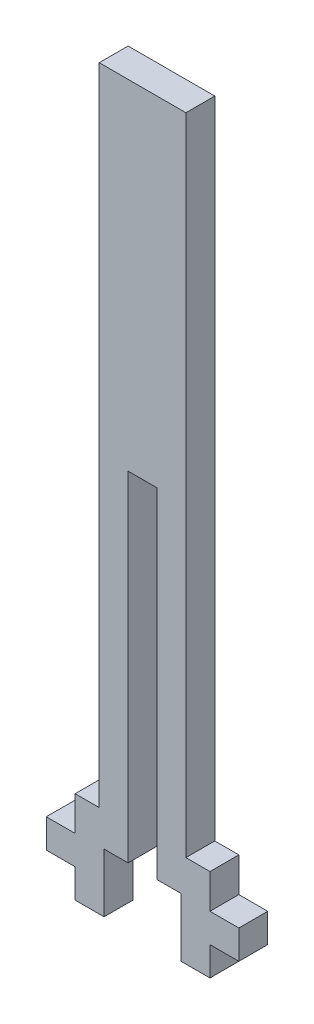
SolidWorks part; units mm, degrees
material "Plain Carbon Steel"
ref_plane "Front Plane" through (0, 0, 0) normal (0, 0, 1) x (1, 0, 0)
ref_plane "Top Plane" through (0, 0, 0) normal (0, 1, 0) x (1, 0, 0)
ref_plane "Right Plane" through (0, 0, 0) normal (1, 0, 0) x (0, 0, -1)
sketch "스케치1" plane through (0, 0, 0) normal (0, 0, 1) x (1, 0, 0)
  line L0 (0, 0) -> (0, -32.1815) construction
  line L1 (-7, -38.2815) -> (7, -38.2815) construction
  line L2 (-7, -38.2815) -> (-7, 38.2815) construction
  line L3 (-7, 38.2815) -> (7, 38.2815) construction
  line L4 (7, -38.2815) -> (7, 38.2815) construction
  line L5 (-7, -38.2815) -> (7, 38.2815) construction
  line L6 (-7, 38.2815) -> (7, -38.2815) construction
  line L7 (-4, -38.2815) -> (4, -38.2815) construction
  line L8 (-4, -38.2815) -> (-4, -32.1815)
  line L9 (-4, -32.1815) -> (4, -32.1815)
  line L10 (4, -38.2815) -> (4, -32.1815)
  line L11 (-4, -38.2815) -> (4, -32.1815) construction
  line L12 (-4, -32.1815) -> (4, -38.2815) construction
  line L13 (4.5, -28.7065) -> (-4.5, -28.7065) construction
  line L14 (7, -28.7065) -> (4.5, -28.7065)
  line L15 (7, -28.7065) -> (7, 38.2815) construction
  line L16 (7, 38.2815) -> (4.5, 38.2815) construction
  line L17 (4.5, -28.7065) -> (4.5, 38.2815) construction
  line L18 (7, -28.7065) -> (4.5, 38.2815) construction
  line L19 (7, 38.2815) -> (4.5, -28.7065) construction
  line L20 (-4.5, 38.2815) -> (-7, 38.2815) construction
  line L21 (-4.5, 38.2815) -> (-4.5, -28.7065) construction
  line L22 (-4.5, -28.7065) -> (-7, -28.7065)
  line L23 (-7, 38.2815) -> (-7, -28.7065) construction
  line L24 (-4.5, 38.2815) -> (-7, -28.7065) construction
  line L25 (-4.5, -28.7065) -> (-7, 38.2815) construction
  line L26 (4, -38.2815) -> (7, -38.2815)
  line L27 (-1.5, 28.7065) -> (1.5, 28.7065) construction
  line L28 (-1.5, 28.7065) -> (-1.5, -28.7065) construction
  line L29 (-1.5, -28.7065) -> (1.5, -28.7065) construction
  line L30 (1.5, 28.7065) -> (1.5, -28.7065) construction
  line L31 (-1.5, 28.7065) -> (1.5, -28.7065) construction
  line L32 (-1.5, -28.7065) -> (1.5, 28.7065) construction
  line L33 (7, -38.2815) -> (7, -28.7065)
  line L34 (-7, -28.7065) -> (-7, -38.2815)
  line L35 (-7, -38.2815) -> (-4, -38.2815)
  line L36 (-4.5, 38.2815) -> (-7, 38.2815) construction
  line L37 (-7, 38.2815) -> (-7, -38.2815)
  line L38 (4.5, 38.2815) -> (7, 38.2815) construction
  line L39 (-4.5, -28.7065) -> (-4.5, 38.2815)
  line L40 (4.5, 38.2815) -> (4.5, -28.7065)
  line L41 (-4.5, 38.2815) -> (4.5, 38.2815)
  point P0 (0, 0)
  point P10 (0, -35.2315)
  point P16 (5.75, 4.7875)
  point P20 (-5.75, 4.7875)
  dimension "D1" = 66.988
  dimension "D2" = 3
  dimension "D3" = 8
  dimension "D4" = 6.1
  dimension "D5" = 3
  dimension "D6" = 3.475
  dimension "D7" = 3
extrude "보스-돌출1" add sketch "스케치1" along normal blind 3 contours L41 L39 L22 L34 L35 L8 L9 L10 L26 L33 L14 L40
sketch "스케치2" plane through (0, 0, 0) normal (0, 0, -1) x (-1, 0, 0)
  line L0 (0, 38.2815) -> (0, -32.1815) construction
  line L1 (4.5, 38.2815) -> (-4.5, 38.2815) construction
  line L2 (4, -32.1815) -> (-4, -32.1815) construction
  line L4 (-1.5, -32.1815) -> (1.5, -32.1815)
  line L5 (-1.5, -32.1815) -> (-1.5, 3.05)
  line L6 (-1.5, 3.05) -> (1.5, 3.05)
  line L7 (1.5, -32.1815) -> (1.5, 3.05)
  line L8 (-1.5, -32.1815) -> (1.5, 3.05) construction
  line L9 (-1.5, 3.05) -> (1.5, -32.1815) construction
  point P6 (0, -14.5658)
  point P11 (0, 3.05)
  dimension "D1" = 3
extrude "컷-돌출1" cut sketch "스케치2" against normal up to surface (3 mm away) up to face at (0, -21.3127, 3)
sketch "스케치3" plane through (0, 0, 3) normal (0, 0, 1) x (1, 0, 0)
  line L0 (-7, -28.7065) -> (-7, -38.2815) construction
  line L1 (-7, -32.2815) -> (-10, -32.2815)
  line L2 (-7, -32.2815) -> (-7, -35.2815)
  line L3 (-7, -35.2815) -> (-10, -35.2815)
  line L4 (-10, -32.2815) -> (-10, -35.2815)
  line L5 (-7, -32.2815) -> (-10, -35.2815) construction
  line L6 (-7, -35.2815) -> (-10, -32.2815) construction
  line L7 (7, -38.2815) -> (7, -28.7065) construction
  line L8 (7, -32.2815) -> (10, -32.2815)
  line L9 (7, -32.2815) -> (7, -35.2815)
  line L10 (7, -35.2815) -> (10, -35.2815)
  line L11 (10, -32.2815) -> (10, -35.2815)
  line L12 (7, -32.2815) -> (10, -35.2815) construction
  line L13 (7, -35.2815) -> (10, -32.2815) construction
  line L14 (-7, -38.2815) -> (-4, -38.2815) construction
  line L15 (4, -38.2815) -> (7, -38.2815) construction
  point P4 (-8.5, -33.7815)
  point P11 (8.5, -33.7815)
  dimension "D1" = 3
  dimension "D2" = 3
  dimension "D3" = 3
  dimension "D4" = 3
  dimension "D5" = 3
  dimension "D6" = 3
extrude "보스-돌출2" add sketch "스케치3" against normal blind 3
